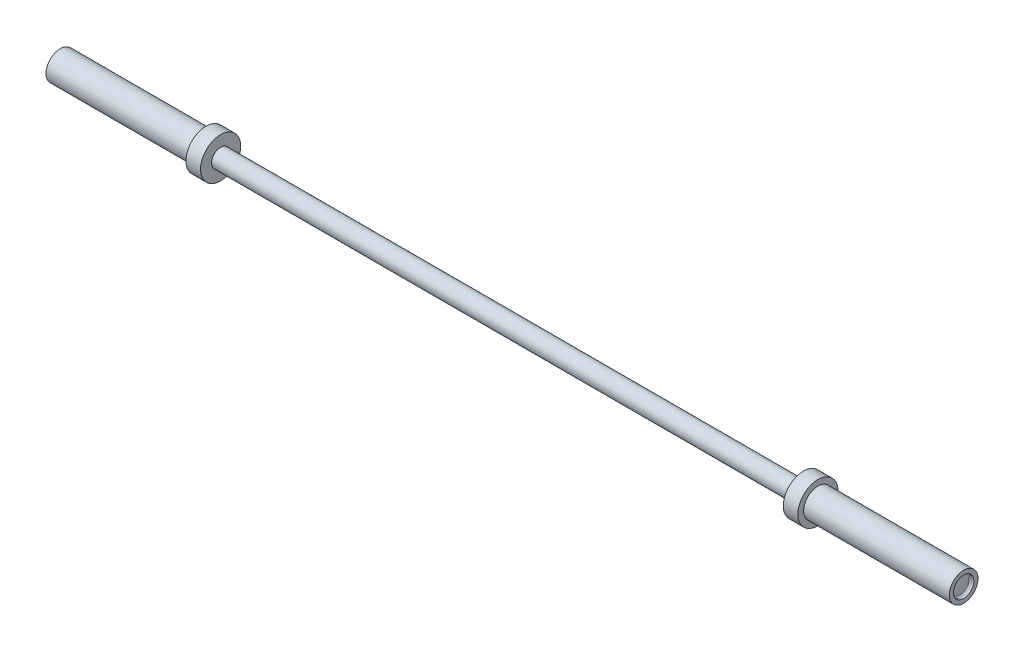
SolidWorks part; units mm, degrees
ref_plane "Front Plane" through (0, 0, 0) normal (0, 0, 1) x (1, 0, 0)
ref_plane "Top Plane" through (0, 0, 0) normal (0, 1, 0) x (1, 0, 0)
ref_plane "Right Plane" through (0, 0, 0) normal (1, 0, 0) x (0, 0, -1)
sketch "Sketch1" plane through (0, 0, 0) normal (1, 0, 0) x (0, 0, -1)
  circle A0 centre (0, 0) radius 15.875
  dimension "D1" = 31.75
extrude "Boss-Extrude1" add sketch "Sketch1" along normal blind 1016
sketch "Sketch2" plane through (1016, 0, 0) normal (1, 0, 0) x (0, 0, -1)
  circle A0 centre (0, 0) radius 35
  dimension "D1" = 70
extrude "Boss-Extrude2" add sketch "Sketch2" along normal blind 25.4
sketch "Sketch3" plane through (0, 0, 0) normal (-1, 0, 0) x (0, 0, 1)
  circle A0 centre (0, 0) radius 35
  dimension "D1" = 70
extrude "Boss-Extrude3" add sketch "Sketch3" along normal blind 25.4
sketch "Sketch4" plane through (1041.4, 0, 0) normal (1, 0, 0) x (0, 0, -1)
  circle A0 centre (0, 0) radius 25
  dimension "D1" = 50
extrude "Boss-Extrude4" add sketch "Sketch4" along normal blind 254
sketch "Sketch5" plane through (-25.4, 0, 0) normal (-1, 0, 0) x (0, 0, 1)
  circle A0 centre (0, 0) radius 25
  dimension "D1" = 50
extrude "Boss-Extrude5" add sketch "Sketch5" along normal blind 254
sketch "Sketch6" plane through (-279.4, 0, 0) normal (-1, 0, 0) x (0, 0, 1)
  circle A0 centre (0, 0) radius 17.78
extrude "Cut-Extrude1" cut sketch "Sketch6" against normal blind 6.35
sketch "Sketch7" plane through (1295.4, 0, 0) normal (1, 0, 0) x (0, 0, -1)
  circle A0 centre (0, 0) radius 17.78
extrude "Cut-Extrude2" cut sketch "Sketch7" against normal blind 6.35
fillet "Fillet1" radius 2.54 2 edges at (1289.05, 0, -17.78) (-273.05, 0, 17.78)
